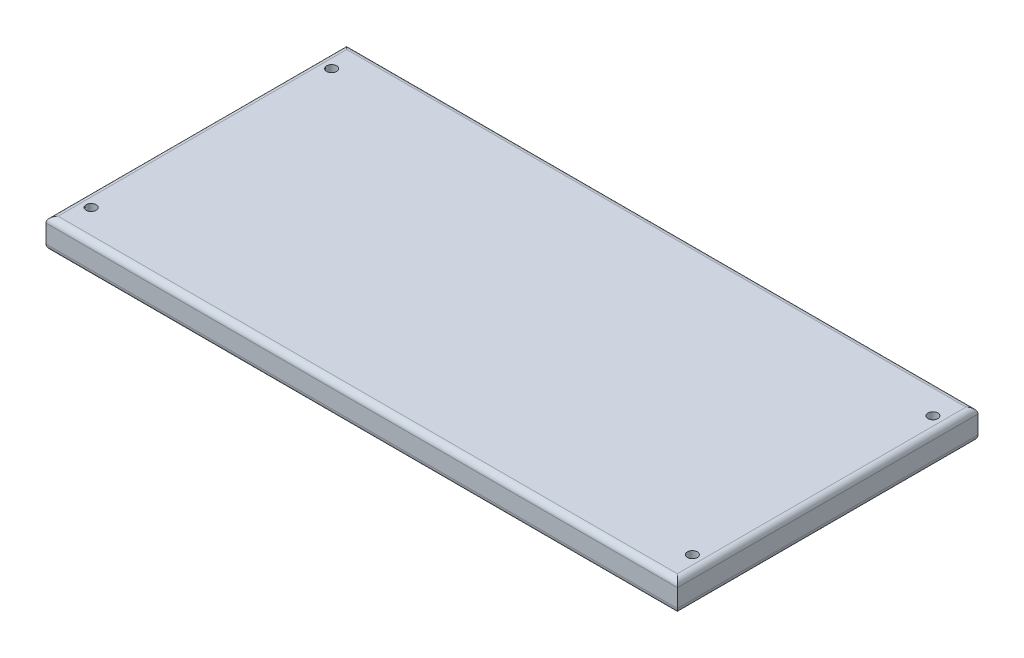
SolidWorks part; units mm, degrees
ref_plane "前视基准面" through (0, 0, 0) normal (0, 0, 1) x (1, 0, 0)
ref_plane "上视基准面" through (0, 0, 0) normal (0, 1, 0) x (1, 0, 0)
ref_plane "右视基准面" through (0, 0, 0) normal (1, 0, 0) x (0, 0, -1)
other "Configuration Table"
sketch "草图1" plane through (0, 0, 0) normal (0, 1, 0) x (1, 0, 0)
  line L1 (-210, 100) -> (0, 100)
  line L2 (-210, 100) -> (-210, 0)
  line L3 (-210, 0) -> (0, 0)
  line L4 (0, 100) -> (0, 0)
  point P4 (0, 0)
  dimension "D1" = 210
  dimension "D2" = 100
extrude "凸台-拉伸1" add sketch "草图1" along normal blind 10
fillet "圆角1" radius 2 8 edges at (-105, 0, 0) (0, 0, -50) (-105, 0, -100) (-210, 0, -50) (-105, 10, -100) (0, 10, -50) (-105, 10, 0) (-210, 10, -50)
sketch "草图2" plane through (0, 10, 0) normal (0, 1, 0) x (1, 0, 0)
  circle A1 centre (-205, 10) radius 1.65
  circle A2 centre (-205, 10) radius 1.65
  circle A3 centre (-205, 90) radius 1.65
  circle A4 centre (-205, 90) radius 1.65
  circle A5 centre (-5, 90) radius 1.65
  circle A6 centre (-5, 90) radius 1.65
  circle A7 centre (-5, 10) radius 1.65
  circle A8 centre (-5, 10) radius 1.65
  dimension "D1" = 0
  dimension "D2" = 0
  dimension "D3" = 0
  dimension "D4" = 0
extrude "切除-拉伸1" cut sketch "草图2" against normal through all
